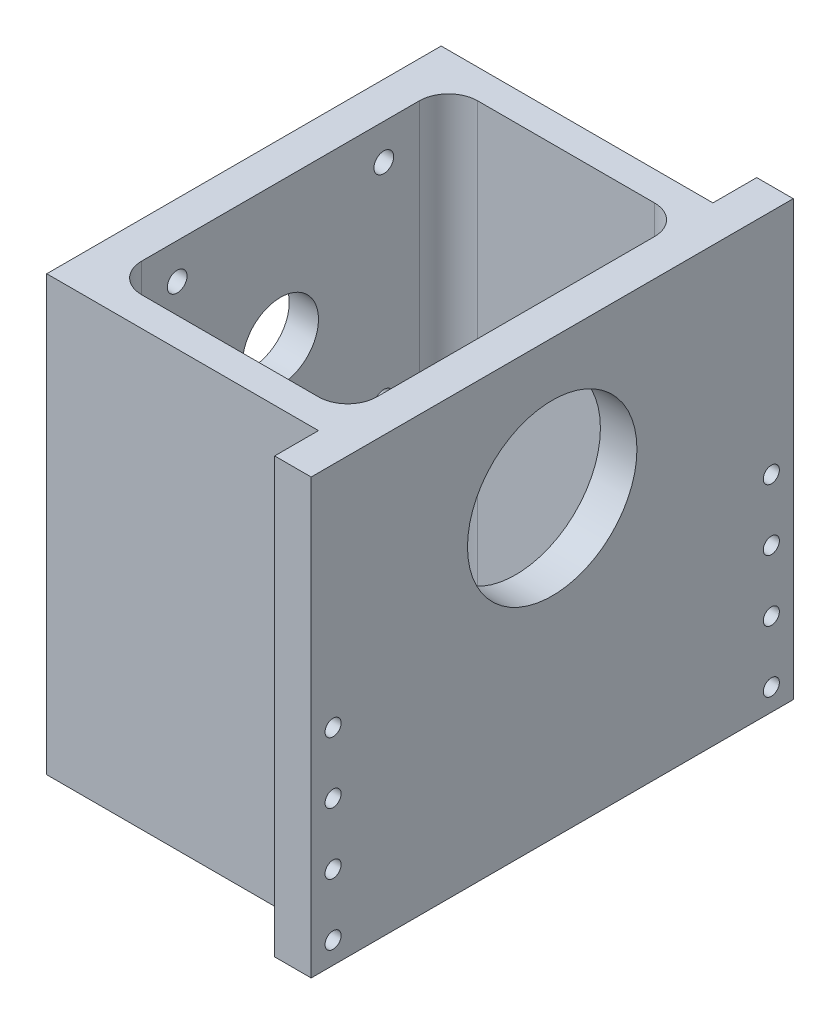
SolidWorks part; units mm, degrees
ref_plane "前视基准面" through (0, 0, 0) normal (0, 0, 1) x (1, 0, 0)
ref_plane "上视基准面" through (0, 0, 0) normal (0, 1, 0) x (1, 0, 0)
ref_plane "右视基准面" through (0, 0, 0) normal (1, 0, 0) x (0, 0, -1)
other "Configuration Table"
sketch "草图4" plane through (0, 0, 0) normal (0, 1, 0) x (1, 0, 0)
  line L1 (-233.3205, 0) -> (-233.3205, 152.4085) construction
  line L2 (-258.3205, -83.2249) -> (-258.3205, -53.2249)
  line L3 (-258.3205, -383.2249) -> (-233.3205, -383.2249)
  line L4 (-258.3205, -383.2249) -> (-258.3205, -353.2249)
  line L5 (-258.3205, -53.2249) -> (-233.3205, -53.2249)
  line L6 (-233.3205, -383.2249) -> (-233.3205, -53.2249)
  line L7 (-258.3205, -383.2249) -> (-233.3205, -53.2249) construction
  line L8 (-258.3205, -53.2249) -> (-233.3205, -383.2249) construction
  line L9 (-444.3205, -353.2249) -> (-258.3205, -353.2249)
  line L10 (-444.3205, -353.2249) -> (-444.3205, -83.2249)
  line L11 (-444.3205, -83.2249) -> (-258.3205, -83.2249)
  line L12 (-258.3205, -313.2249) -> (-258.3205, -123.2249)
  line L13 (-444.3205, -353.2249) -> (-258.3205, -83.2249) construction
  line L14 (-444.3205, -83.2249) -> (-258.3205, -353.2249) construction
  line L15 (-399.3205, -333.2249) -> (-278.3205, -333.2249)
  line L16 (-419.3205, -313.2249) -> (-419.3205, -123.2249)
  line L17 (-399.3205, -103.2249) -> (-278.3205, -103.2249)
  line L19 (-419.3205, -333.2249) -> (-258.3205, -103.2249) construction
  line L20 (-419.3205, -103.2249) -> (-258.3205, -333.2249) construction
  arc A0 (-258.3205, -123.2249) -> (-278.3205, -103.2249) centre (-278.3205, -123.2249) ccw
  arc A1 (-419.3205, -123.2249) -> (-399.3205, -103.2249) centre (-399.3205, -123.2249) cw
  arc A2 (-399.3205, -333.2249) -> (-419.3205, -313.2249) centre (-399.3205, -313.2249) cw
  arc A3 (-278.3205, -333.2249) -> (-258.3205, -313.2249) centre (-278.3205, -313.2249) ccw
  point P2 (-351.3205, -218.2249)
  point P4 (-245.8205, -218.2249)
  point P14 (-338.8205, -218.2249)
  dimension "D7" = 20
  dimension "D8" = 20
  dimension "D1" = 25
  dimension "D2" = 330
  dimension "D3" = 270
  dimension "D4" = 211
  dimension "D5" = 25
  dimension "D6" = 20
  dimension "D9" = 161
  dimension "D10" = 20
extrude "凸台-拉伸1" add sketch "草图4" along normal blind 297
sketch "草图6" plane through (-444.3205, 0, 0) normal (-1, 0, 0) x (0, 0, 1)
  line L0 (218.2249, 0) -> (218.2249, 202) construction
  line L2 (83.2249, 0) -> (353.2249, 0) construction
  circle A0 centre (218.2249, 202) radius 57.15
  dimension "D1" = 114.3
extrude "切除-拉伸1" cut sketch "草图6" against normal blind 5
sketch "草图7" plane through (-439.3205, 0, 0) normal (-1, 0, 0) x (0, 0, 1)
  circle A0 centre (218.2249, 202) radius 26
  dimension "D1" = 52
extrude "切除-拉伸2" cut sketch "草图7" against normal up to next
sketch "草图8" plane through (-233.3205, 0, 0) normal (1, 0, 0) x (0, 0, -1)
  line L0 (-218.2249, 0) -> (-218.2249, 202) construction
  line L1 (-383.2249, 0) -> (-53.2249, 0) construction
  circle A0 centre (-218.2249, 202) radius 58
  dimension "D1" = 116
extrude "切除-拉伸3" cut sketch "草图8" against normal up to next
sketch "草图10" plane through (-258.3205, 0, 0) normal (-1, 0, 0) x (0, 0, 1)
  line L0 (218.2249, 0) -> (218.2249, 141) construction
  circle A0 centre (368.2249, 15) radius 5.5
  circle A1 centre (368.2249, 57) radius 5.5
  circle A2 centre (368.2249, 99) radius 5.5
  circle A3 centre (368.2249, 141) radius 5.5
  circle A4 centre (68.2249, 141) radius 5.5
  circle A5 centre (68.2249, 15) radius 5.5
  circle A6 centre (68.2249, 57) radius 5.5
  circle A7 centre (68.2249, 99) radius 5.5
  dimension "D1" = 4
extrude "切除-拉伸4" cut sketch "草图10" against normal up to next
sketch "草图11" plane through (-444.3205, 0, 0) normal (-1, 0, 0) x (0, 0, 1)
  circle A0 centre (218.2249, 202) radius 100 construction
  point P9 (147.5149, 272.7114)
  dimension "D1" = 200
hole_wizard "M12 间隙孔1" positions "草图16" profile "草图17" hole size "M12" standard "GB"
sketch "草图16" plane through (-444.3205, 0, 0) normal (-1, 0, 0) x (0, 0, 1)
  point P0 (147.5149, 272.7114)
sketch "草图17" plane through (-444.3205, 272.7114, 147.5149) normal (0, 1, 0) x (0, 0, 1)
  line L0 (0, 0) -> (0, 25)
  line L1 (0, 25) -> (6.75, 25)
  line L2 (6.75, 25) -> (6.75, 0)
  line L5 (6.75, 0) -> (0, 0)
  line L11 (0, -6.35) -> (0, 107.95) construction
  dimension "通孔孔直径" = 13.5
  dimension "通孔孔深度" = 25
pattern_circular "阵列(圆周)1" count 4 every 90 about axis through (0, 202, 218.2249) along (1, 0, 0) of "M12 间隙孔1"
